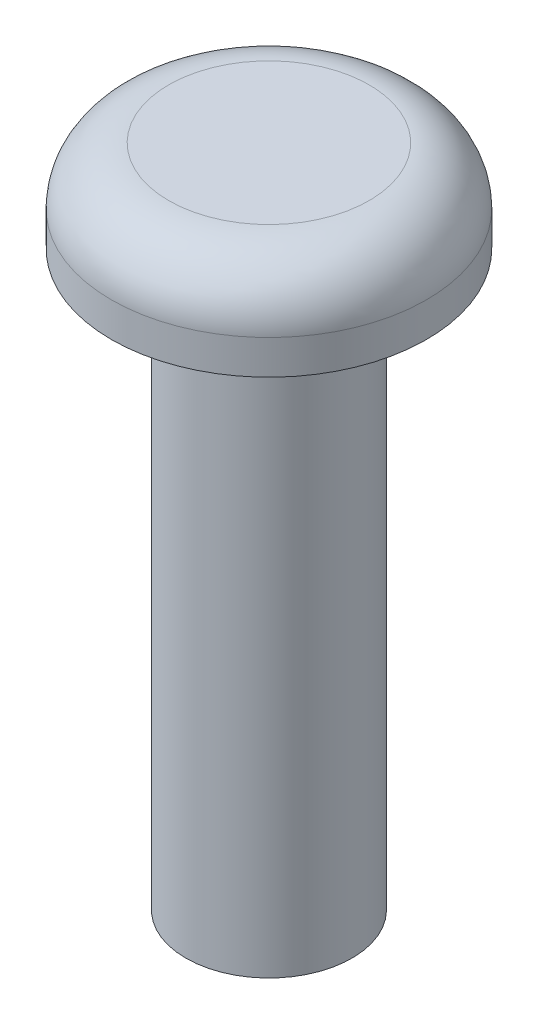
SolidWorks part; units mm, degrees
ref_plane "Front Plane" through (0, 0, 0) normal (0, 0, 1) x (1, 0, 0)
ref_plane "Top Plane" through (0, 0, 0) normal (0, 1, 0) x (1, 0, 0)
ref_plane "Right Plane" through (0, 0, 0) normal (1, 0, 0) x (0, 0, -1)
sketch "Sketch1" plane through (0, 0, 0) normal (0, 1, 0) x (1, 0, 0)
  circle A0 centre (0, 0) radius 1.45
  dimension "D1" = 2.9
extrude "Boss-Extrude1" add sketch "Sketch1" against normal blind 10
sketch "Sketch2" plane through (0, 0, 0) normal (0, 1, 0) x (1, 0, 0)
  circle A0 centre (0, 0) radius 2.75
  dimension "D1" = 5.5
extrude "Boss-Extrude2" add sketch "Sketch2" along normal blind 1.6
fillet "Fillet1" radius 1 1 edges at (0, 1.6, 2.75)
